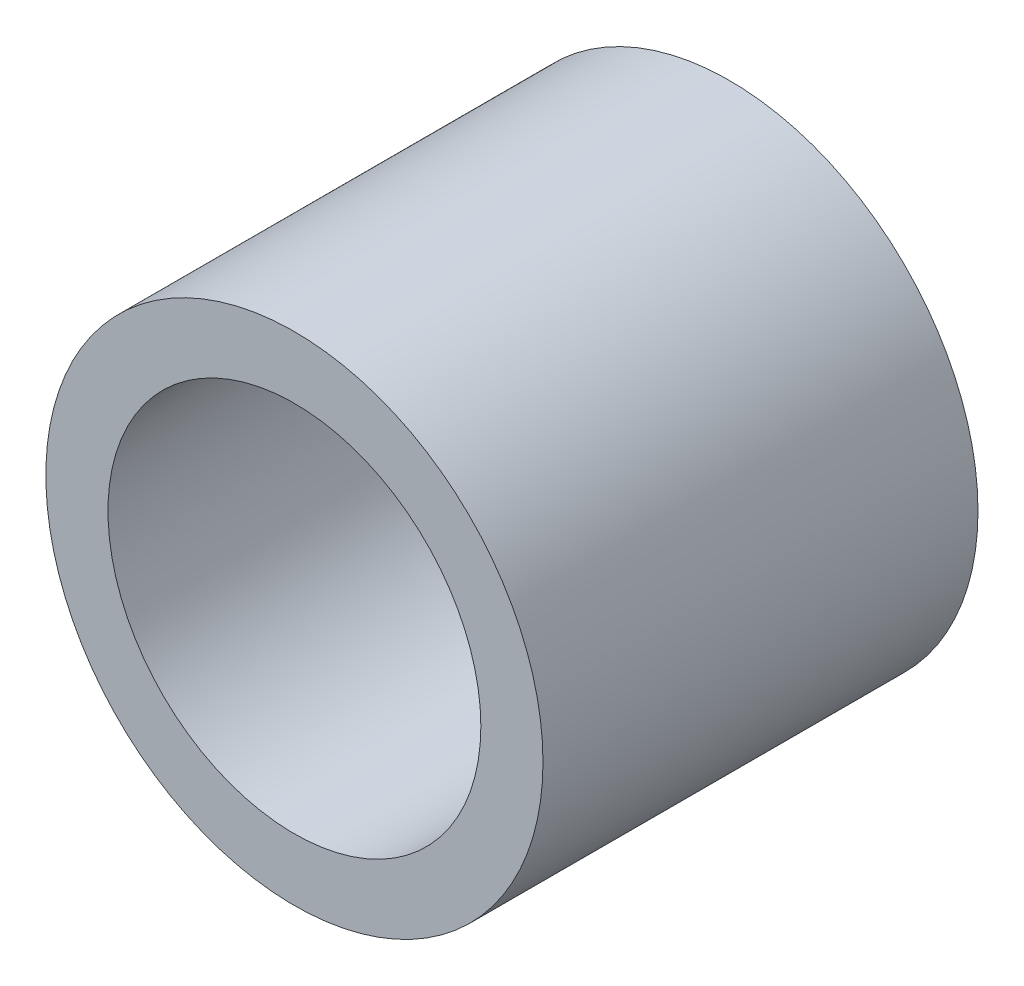
SolidWorks part; units mm, degrees
ref_plane "Plan de face" through (0, 0, 0) normal (0, 0, 1) x (1, 0, 0)
ref_plane "Plan de dessus" through (0, 0, 0) normal (0, 1, 0) x (1, 0, 0)
ref_plane "Plan de droite" through (0, 0, 0) normal (1, 0, 0) x (0, 0, -1)
sketch "Esquisse1" plane through (0, 0, 0) normal (0, 0, 1) x (1, 0, 0)
  circle A0 centre (0, 0) radius 4
  circle A1 centre (0, 0) radius 3
  dimension "D1" = 8
  dimension "D2" = 6
extrude "Boss.-Extru.1" add sketch "Esquisse1" along normal blind 7
